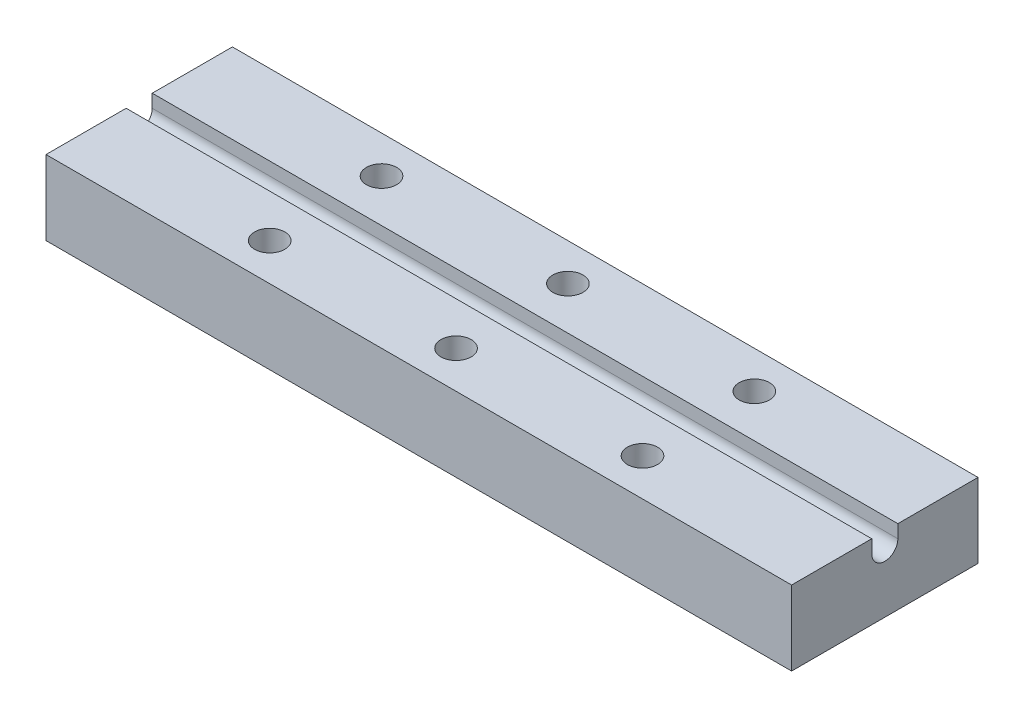
SolidWorks part; units mm, degrees
material "Copper"
ref_plane "Front Plane" through (0, 0, 0) normal (0, 0, 1) x (1, 0, 0)
ref_plane "Top Plane" through (0, 0, 0) normal (0, 1, 0) x (1, 0, 0)
ref_plane "Right Plane" through (0, 0, 0) normal (1, 0, 0) x (0, 0, -1)
sketch "Sketch1" plane through (0, 0, 0) normal (0, 1, 0) x (1, 0, 0)
  line L1 (0, 0) -> (200, 0)
  line L2 (0, 0) -> (0, 50)
  line L3 (0, 50) -> (200, 50)
  line L4 (200, 0) -> (200, 50)
  dimension "D1" = 200
  dimension "D2" = 50
extrude "Boss-Extrude1" add sketch "Sketch1" along normal blind 20
sketch "Sketch2" plane through (0, 0, 0) normal (-1, 0, 0) x (0, 0, 1)
  line L0 (-50, 20) -> (0, 20)
  line L1 (-25, 20) -> (-25, 0)
  line L2 (-50, 0) -> (0, 0) construction
  line L3 (-28.5, 16.5) -> (-28.5, 20)
  line L4 (-21.5, 16.5) -> (-21.5, 20)
  circle A0 centre (-25, 16.5) radius 3.5
  dimension "D1" = 7
extrude "Cut-Extrude1" cut sketch "Sketch2" against normal blind 221 and the other way blind 30 contours A0 L0 L3 | A0 L1 | A0 L4 L0 | L1 A0
ref_plane "Plane1" through (0, 0, 0) normal (0, -1, 0) x (-1, 0, 0)
sketch "Sketch3" plane through (0, 0, 0) normal (0, -1, 0) x (1, 0, 0)
  line L0 (200, 0) -> (0, 0)
  line L1 (100, 0) -> (100, -50)
  line L2 (200, -50) -> (0, -50) construction
  line L3 (200, 0) -> (100, 0)
  line L4 (100, 0) -> (0, 0)
  line L6 (100, 0) -> (0, 0)
  line L7 (50, 0) -> (50, -50)
  line L8 (200, -21.5) -> (0, -21.5)
  line L9 (200, -28.5) -> (0, -28.5)
  line L10 (150, 0) -> (150, -20)
  line L11 (150, -30) -> (150, -50)
  circle A0 centre (150, -10) radius 4.05
  circle A1 centre (150, -40) radius 4.05
  circle A2 centre (100, -40) radius 4.05
  circle A3 centre (100, -10) radius 4.05
  circle A4 centre (50, -40) radius 4.05
  circle A5 centre (50, -10) radius 4.05
  dimension "D1" = 8.1
  dimension "D2" = 8.1
  dimension "D4" = 10
  dimension "D5" = 10
  dimension "D3" = 3
extrude "Cut-Extrude2" cut sketch "Sketch3" against normal blind 67 contours L1 A3 | L1 A3 | L7 A5 | L7 A5 | A4 | A2 | A1 | A0
